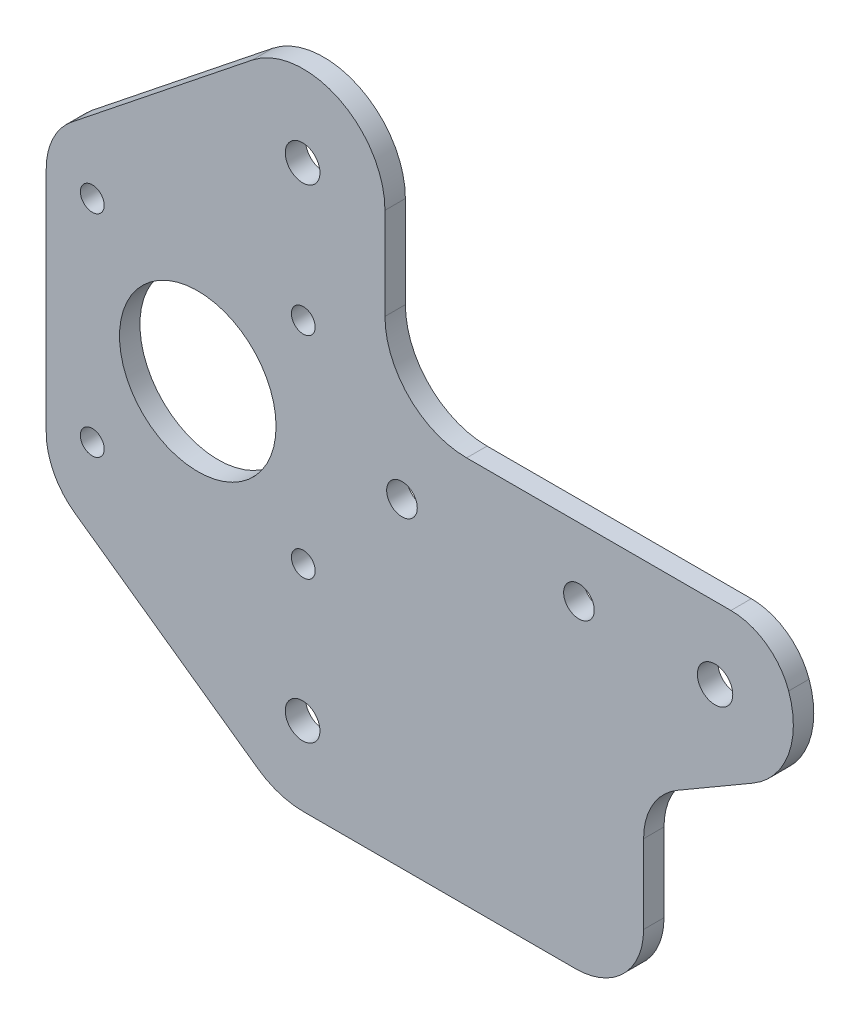
SolidWorks part; units mm, degrees
ref_plane "Alzado" through (0, 0, 0) normal (0, 0, 1) x (1, 0, 0)
ref_plane "Planta" through (0, 0, 0) normal (0, 1, 0) x (1, 0, 0)
ref_plane "Vista lateral" through (0, 0, 0) normal (1, 0, 0) x (0, 0, -1)
ref_plane "Plano1" through (0, 0, 0) normal (0, 0, -1) x (-1, 0, 0)
sketch "Croquis1" plane through (0, 0, 0) normal (0, 0, -1) x (-1, 0, 0)
  line L0 (-81.5363, -10.3712) -> (-70.4697, -16.8123)
  line L1 (-65.5, -25.455) -> (-65.5, -37)
  line L2 (-55.5, -47) -> (-15.5, -47)
  line L3 (-8.8483, -44.8811) -> (18.0483, -25.8101)
  line L4 (22.2642, -17.6526) -> (22.2642, 15.9197)
  line L5 (18.4986, 23.7384) -> (-8.0187, 44.8825)
  line L6 (-27.5, 35.5) -> (-27.5, 22)
  line L7 (-39.5, 10) -> (-78.3284, 10)
  circle A0 centre (-30, 0) radius 2.25
  circle A1 centre (-15.4, -35.5) radius 2.55
  circle A2 centre (-15.4, 35.5) radius 2.55
  circle A3 centre (15.5, 15.5) radius 1.75
  circle A4 centre (15.5, -15.5) radius 1.75
  circle A5 centre (-15.5, -15.5) radius 1.75
  circle A6 centre (-15.5, 15.5) radius 1.75
  circle A7 centre (0, 0) radius 11.5
  circle A8 centre (-56, 0) radius 2.25
  arc A9 (-86.8137, 4) -> (-81.5363, -10.3712) centre (-75.5, 0) ccw
  arc A10 (-70.4697, -16.8123) -> (-65.5, -25.455) centre (-75.5, -25.455) cw
  arc A11 (-65.5, -37) -> (-55.5, -47) centre (-55.5, -37) ccw
  arc A12 (-15.5, -47) -> (-8.8483, -44.8811) centre (-15.5, -35.5) ccw
  arc A13 (18.0483, -25.8101) -> (22.2642, -17.6526) centre (12.2642, -17.6526) ccw
  arc A14 (22.2642, 15.9197) -> (18.4986, 23.7384) centre (12.2642, 15.9197) ccw
  arc A15 (-8.0187, 44.8825) -> (-27.5, 35.5) centre (-15.5, 35.5) ccw
  arc A16 (-27.5, 22) -> (-39.5, 10) centre (-39.5, 22) cw
  arc A17 (-78.3284, 10) -> (-86.8137, 4) centre (-78.3284, 1) ccw
  circle A18 centre (-76, -0.5745) radius 2.6
extrude "Saliente-Extruir1" add sketch "Croquis1" against normal blind 3
